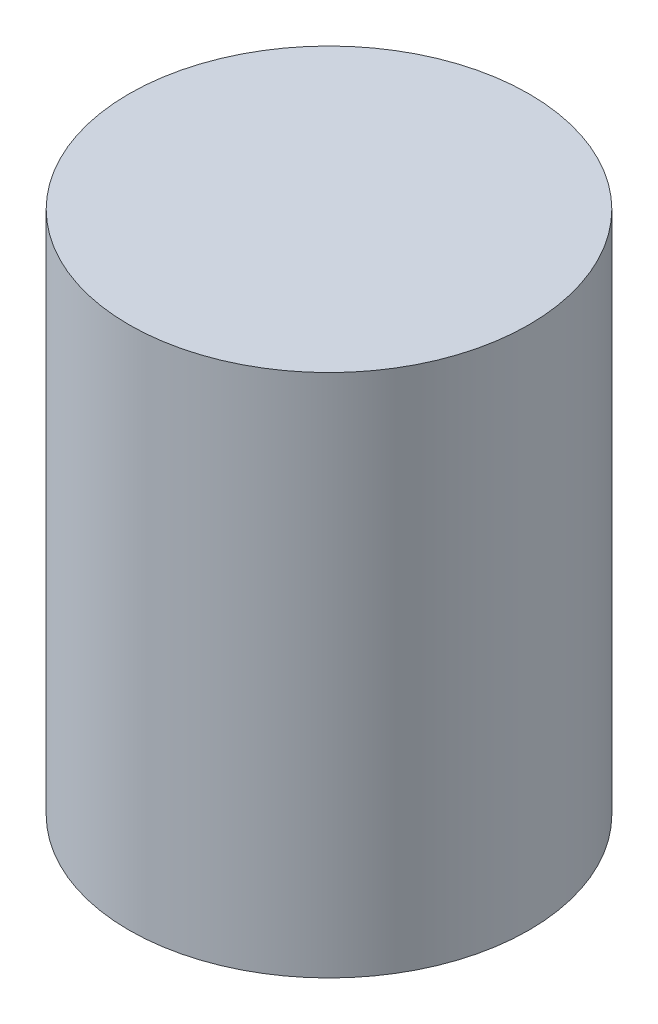
SolidWorks part; units mm, degrees
material "1060-O (SS)"
ref_plane "Front Plane" through (0, 0, 0) normal (0, 0, 1) x (1, 0, 0)
ref_plane "Top Plane" through (0, 0, 0) normal (0, 1, 0) x (1, 0, 0)
ref_plane "Right Plane" through (0, 0, 0) normal (1, 0, 0) x (0, 0, -1)
sketch "Sketch1" plane through (0, 0, 0) normal (0, 1, 0) x (1, 0, 0)
  circle A0 centre (0, 0) radius 24.9
  dimension "D1" = 49.8
extrude "Boss-Extrude1" add sketch "Sketch1" along normal blind 65.278 contours A0
